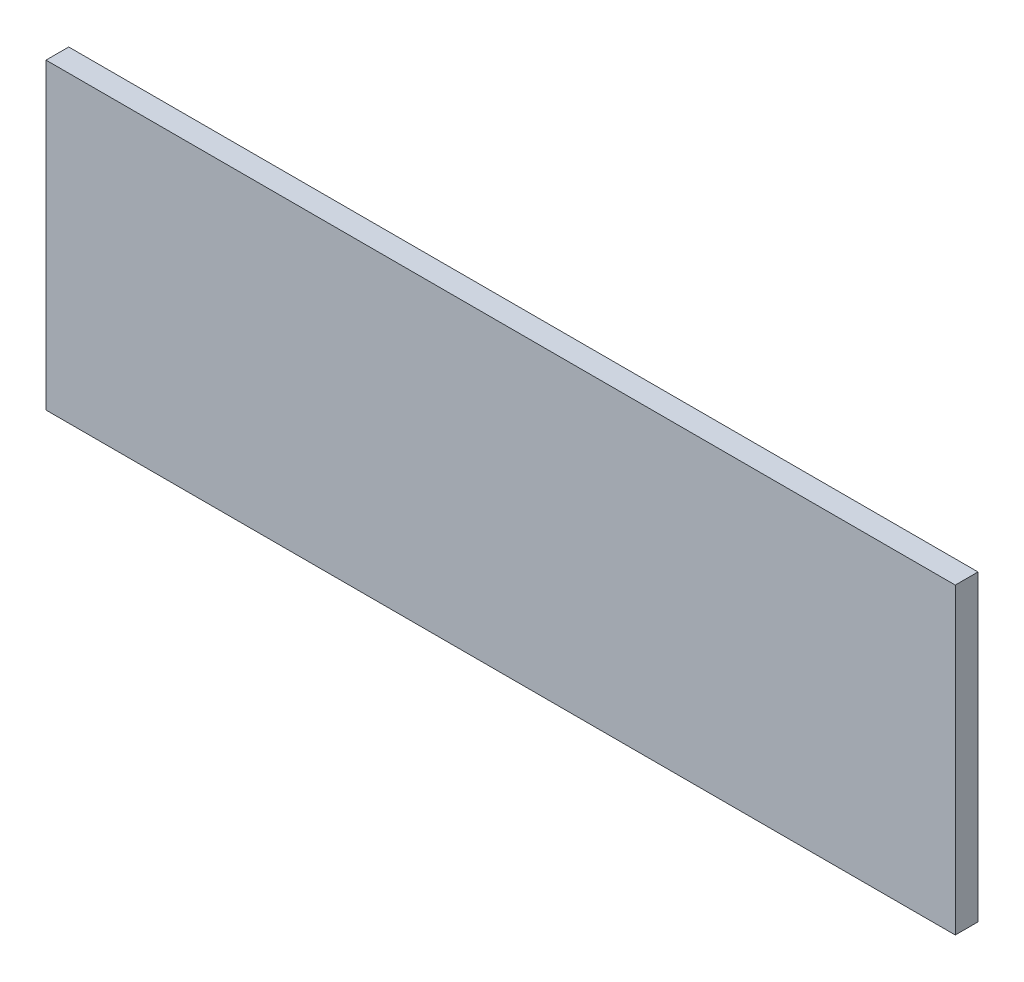
SolidWorks part; units mm, degrees
ref_plane "前视基准面" through (0, 0, 0) normal (0, 0, 1) x (1, 0, 0)
ref_plane "上视基准面" through (0, 0, 0) normal (0, 1, 0) x (1, 0, 0)
ref_plane "右视基准面" through (0, 0, 0) normal (1, 0, 0) x (0, 0, -1)
sketch "草图1" plane through (0, 0, 0) normal (0, 0, 1) x (1, 0, 0)
  line L1 (-6000, 2000) -> (6000, 2000)
  line L2 (-6000, 2000) -> (-6000, -2000)
  line L3 (-6000, -2000) -> (6000, -2000)
  line L4 (6000, 2000) -> (6000, -2000)
  line L5 (0, -2000) -> (0, 2000) construction
  line L6 (-6000, 0) -> (6000, 0) construction
  point P0 (0, 0)
  point P4 (6000, 0)
  dimension "D1" = 12000
  dimension "D2" = 4000
extrude "凸台-拉伸1" add sketch "草图1" along normal blind 300
